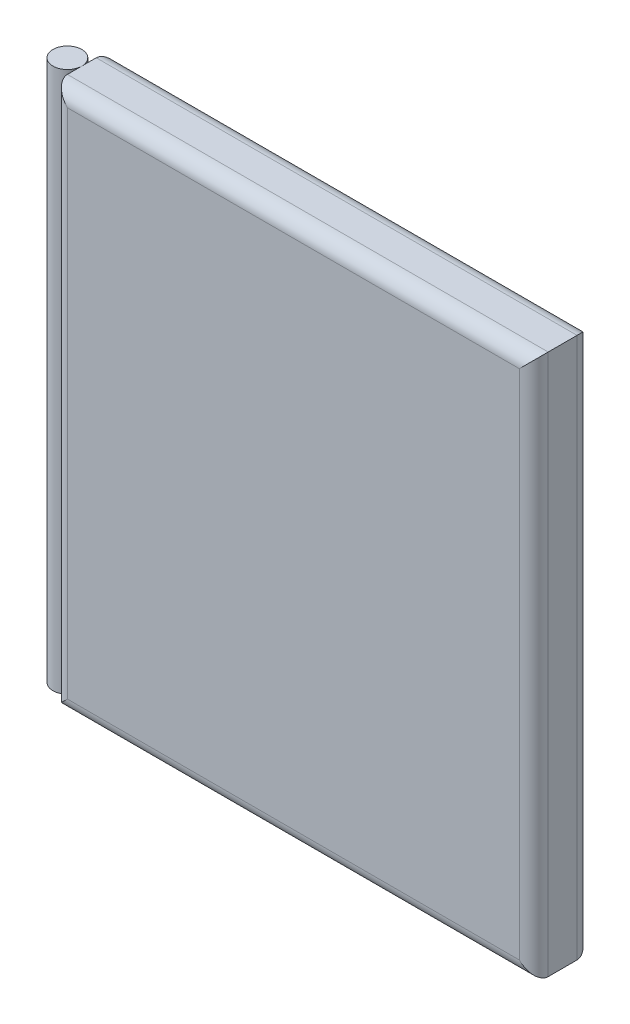
SolidWorks part; units mm, degrees
material "Custom Plastic"
ref_plane "Front Plane" through (0, 0, 0) normal (0, 0, 1) x (1, 0, 0)
ref_plane "Top Plane" through (0, 0, 0) normal (0, 1, 0) x (1, 0, 0)
ref_plane "Right Plane" through (0, 0, 0) normal (1, 0, 0) x (0, 0, -1)
sketch "Sketch2" plane through (0, 0, 0) normal (0, 0, 1) x (1, 0, 0)
  line L1 (-255.9947, 131.1656) -> (410.6053, 131.1656)
  line L2 (-255.9947, 131.1656) -> (-255.9947, -618.8344)
  line L3 (-255.9947, -618.8344) -> (410.6053, -618.8344)
  line L4 (410.6053, 131.1656) -> (410.6053, -618.8344)
  dimension "D1" = 666.6
  dimension "D2" = 750
extrude "Boss-Extrude1" add sketch "Sketch2" along normal blind 80
fillet "Fillet1" radius 20 8 edges at (-255.9947, -243.8344, 80) (-255.9947, -243.8344, 0) (410.6053, -243.8344, 0) (410.6053, -243.8344, 80) (77.3053, -618.8344, 0) (77.3053, -618.8344, 80) (77.3053, 131.1656, 80) (77.3053, 131.1656, 0)
sketch "Sketch3" plane through (0, -618.8344, 0) normal (0, -1, 0) x (-1, 0, 0)
  line L0 (255.9947, -60) -> (255.9947, -20) construction
  circle A0 centre (275.9947, -40) radius 20
  point P4 (255.9947, -40)
extrude "Boss-Extrude2" add sketch "Sketch3" against normal blind 750 separate body
